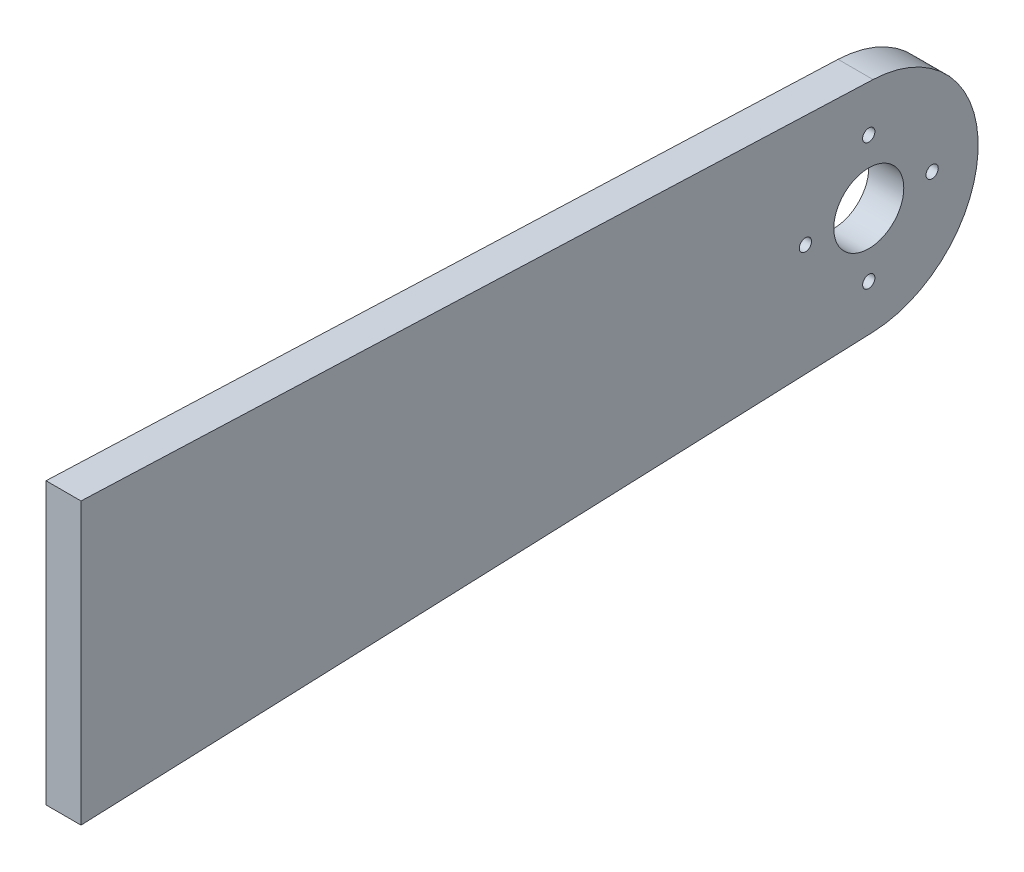
SolidWorks part; units mm, degrees
material "Perspex (TM) GS Acrylic Cast Sheet"
ref_plane "Front Plane" through (0, 0, 0) normal (0, 0, 1) x (1, 0, 0)
ref_plane "Top Plane" through (0, 0, 0) normal (0, 1, 0) x (1, 0, 0)
ref_plane "Right Plane" through (0, 0, 0) normal (1, 0, 0) x (0, 0, -1)
sketch "Sketch1" plane through (0, 0, 0) normal (1, 0, 0) x (0, 0, -1)
  line L0 (-90, 16.0391) -> (-90, -16.0391)
  line L19 (-90, 16.0391) -> (0.4898, 12.4904)
  line L20 (-90, -16.0391) -> (0.4898, -12.4904)
  circle A0 centre (0, 0) radius 4
  circle A1 centre (-7.24, 0) radius 0.7
  circle A2 centre (0, 7.24) radius 0.7
  circle A3 centre (7.24, 0) radius 0.7
  circle A4 centre (0, -7.24) radius 0.7
  arc A5 (0.4898, -12.4904) -> (0.4898, 12.4904) centre (0, 0) ccw
  point P18 (0, 0)
  dimension "D1" = 8
  dimension "D2" = 1.4
  dimension "D5" = 90
  dimension "D9" = 25
  dimension "D3" = 7.24
  dimension "D6" = 4.492
  dimension "D7" = 87.754
  dimension "D4" = 4
extrude "Boss-Extrude1" add sketch "Sketch1" along normal blind 4
sketch "Sketch2" plane through (4, 0, 0) normal (1, 0, 0) x (0, 0, -1)
  line L0 (0, 0) -> (-90, 0) construction
  line L1 (-90, 16.0391) -> (-90, -16.0391) construction
